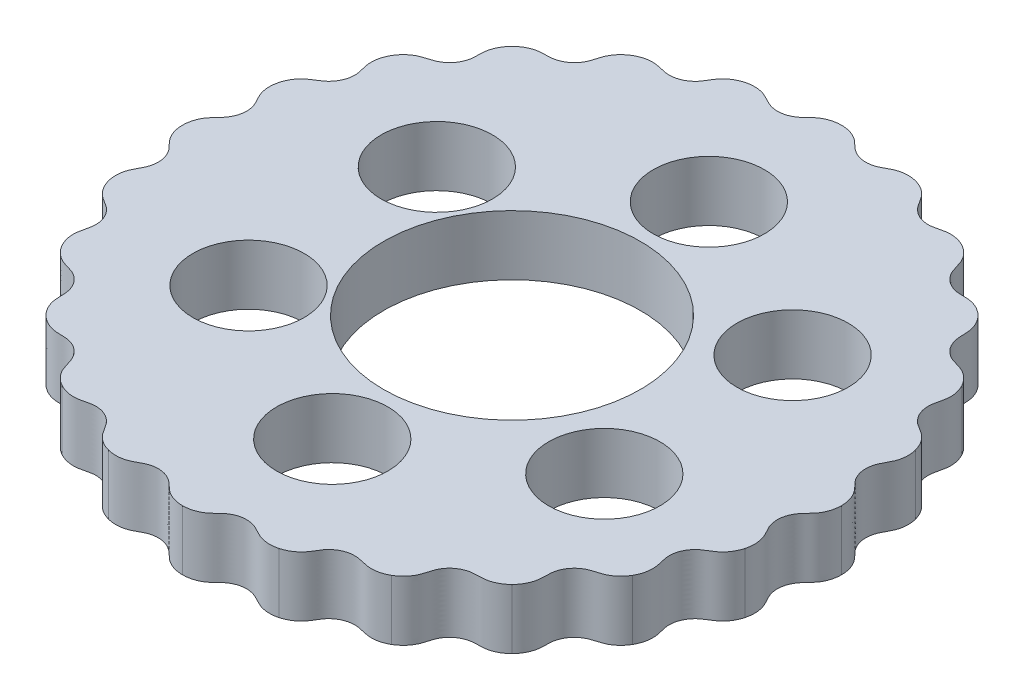
SolidWorks part; units mm, degrees
ref_plane "Front Plane" through (0, 0, 0) normal (0, 0, 1) x (1, 0, 0)
ref_plane "Top Plane" through (0, 0, 0) normal (0, 1, 0) x (1, 0, 0)
ref_plane "Right Plane" through (0, 0, 0) normal (1, 0, 0) x (0, 0, -1)
sketch "Sketch1" plane through (0, 0, 0) normal (0, 1, 0) x (1, 0, 0)
  line L0 (0, 0) -> (-1, 0) construction
  line L1 (40, 0) -> (41, 0) construction
  line L2 (-1, 0) -> (-1, 23) construction
  circle A0 centre (0, 0) radius 40 construction
  circle A1 centre (40, 0) radius 2.5 construction
  circle A2 centre (38.7433, -9.9476) radius 2.5 construction
  circle A3 centre (35.0523, -19.2701) radius 2.5 construction
  circle A4 centre (29.1587, -27.3819) radius 2.5 construction
  circle A5 centre (21.4331, -33.7731) radius 2.5 construction
  circle A6 centre (12.3607, -38.0423) radius 2.5 construction
  circle A7 centre (2.5116, -39.9211) radius 2.5 construction
  circle A8 centre (-7.4953, -39.2915) radius 2.5 construction
  circle A9 centre (-17.0312, -36.1931) radius 2.5 construction
  circle A10 centre (-25.497, -30.8205) radius 2.5 construction
  circle A11 centre (-32.3607, -23.5114) radius 2.5 construction
  circle A12 centre (-37.1911, -14.725) radius 2.5 construction
  circle A13 centre (-39.6846, -5.0133) radius 2.5 construction
  circle A14 centre (-39.6846, 5.0133) radius 2.5 construction
  circle A15 centre (-37.1911, 14.725) radius 2.5 construction
  circle A16 centre (-32.3607, 23.5114) radius 2.5 construction
  circle A17 centre (-25.497, 30.8205) radius 2.5 construction
  circle A18 centre (-17.0312, 36.1931) radius 2.5 construction
  circle A19 centre (-7.4953, 39.2915) radius 2.5 construction
  circle A20 centre (2.5116, 39.9211) radius 2.5 construction
  circle A21 centre (12.3607, 38.0423) radius 2.5 construction
  circle A22 centre (21.4331, 33.7731) radius 2.5 construction
  circle A23 centre (29.1587, 27.3819) radius 2.5 construction
  circle A24 centre (35.0523, 19.2701) radius 2.5 construction
  circle A25 centre (38.7433, 9.9476) radius 2.5 construction
  circle A26 centre (0, 0) radius 38.4 construction
  circle A27 centre (38.637, 10.3528) radius 1.6 construction
  circle A28 centre (39.603, 10.6116) radius 0.25 construction
  circle A29 centre (-1, 0) radius 15
  circle A30 centre (-1, 23) radius 6.5
  circle A31 centre (19.4186, 12.366) radius 6.5
  circle A32 centre (20.4186, -10.634) radius 6.5
  circle A33 centre (1, -23) radius 6.5
  circle A34 centre (-19.4186, -12.366) radius 6.5
  circle A35 centre (-20.4186, 10.634) radius 6.5
  spline S48 degree 3 poles (-38.1881, 9.9647) (-38.1134, 10.2441) (-37.9518, 10.654) (-37.653, 11.1446) (-37.3903, 11.4799) (-37.1455, 11.7256) (-36.9277, 11.9083) (-36.7529, 12.0385) (-36.5906, 12.1462) (-36.4589, 12.2267) (-36.305, 12.3174) (-36.1077, 12.438) (-35.8562, 12.5947) (-35.414, 12.9369) (-35.0082, 13.4243) (-34.7303, 13.9227) (-34.557, 14.4369) (-34.4576, 15.2234) (-34.5769, 15.8673) (-34.6328, 16.0713) (-34.6733, 16.2389) (-34.7113, 16.3925) (-34.7527, 16.5721) (-34.7948, 16.7807) (-34.8258, 16.9881) (-34.85, 17.2627) (-34.8492, 17.6154) (-34.7979, 18.0376) (-34.6627, 18.5948) (-34.4867, 18.9996) (-34.3419, 19.2502) knots -0.000084 -0.000084 -0.000084 -0.000084 0.124937 0.187447 0.249958 0.312468 0.343724 0.374979 0.406234 0.421862 0.437489 0.453117 0.468745 0.484372 0.492186 0.5 0.507814 0.515628 0.531255 0.546883 0.562511 0.578138 0.593766 0.625021 0.656276 0.687532 0.750042 0.812553 0.875063 1.000084 1.000084 1.000084 1.000084
  spline S49 degree 3 poles (-34.3419, 19.2502) (-34.1974, 19.5007) (-33.9353, 19.8548) (-33.5196, 20.2513) (-33.1791, 20.5073) (-32.879, 20.6812) (-32.6214, 20.8013) (-32.4189, 20.8818) (-32.2342, 20.9438) (-32.0861, 20.9876) (-31.914, 21.0353) (-31.6923, 21.1008) (-31.4088, 21.187) (-30.893, 21.4031) (-30.3749, 21.7688) (-29.9775, 22.1783) (-29.677, 22.6302) (-29.3775, 23.3642) (-29.326, 24.017) (-29.3272, 24.2285) (-29.323, 24.4009) (-29.3199, 24.559) (-29.3134, 24.7432) (-29.3001, 24.9557) (-29.2764, 25.164) (-29.2287, 25.4355) (-29.1366, 25.776) (-28.9778, 26.1705) (-28.703, 26.6737) (-28.4282, 27.0192) (-28.2235, 27.2237) knots -0.000084 -0.000084 -0.000084 -0.000084 0.124937 0.187447 0.249958 0.312468 0.343724 0.374979 0.406234 0.421862 0.437489 0.453117 0.468745 0.484372 0.492186 0.5 0.507814 0.515628 0.531255 0.546883 0.562511 0.578138 0.593766 0.625021 0.656276 0.687532 0.750042 0.812553 0.875063 1.000084 1.000084 1.000084 1.000084
  spline S50 degree 3 poles (-28.2235, 27.2237) (-28.0191, 27.4283) (-27.6742, 27.7026) (-27.1701, 27.978) (-26.7749, 28.1371) (-26.4401, 28.2274) (-26.1602, 28.2767) (-25.9437, 28.3021) (-25.7492, 28.3142) (-25.5949, 28.3181) (-25.4163, 28.3197) (-25.1852, 28.3255) (-24.889, 28.3354) (-24.3349, 28.4107) (-23.7398, 28.6298) (-23.25, 28.9226) (-22.8428, 29.2812) (-22.3634, 29.9127) (-22.1448, 30.5299) (-22.0912, 30.7346) (-22.0425, 30.9) (-21.9986, 31.0519) (-21.9447, 31.2282) (-21.8768, 31.43) (-21.8, 31.625) (-21.6836, 31.8749) (-21.5066, 32.18) (-21.251, 32.5199) (-20.8553, 32.9349) (-20.5005, 33.1974) (-20.2498, 33.3421) knots -0.000084 -0.000084 -0.000084 -0.000084 0.124937 0.187447 0.249958 0.312468 0.343724 0.374979 0.406234 0.421862 0.437489 0.453117 0.468745 0.484372 0.492186 0.5 0.507814 0.515628 0.531255 0.546883 0.562511 0.578138 0.593766 0.625021 0.656276 0.687532 0.750042 0.812553 0.875063 1.000084 1.000084 1.000084 1.000084
  spline S51 degree 3 poles (-20.2498, 33.3421) (-19.9994, 33.4868) (-19.5954, 33.6624) (-19.0372, 33.798) (-18.6143, 33.8494) (-18.2675, 33.85) (-17.9843, 33.8252) (-17.7687, 33.7936) (-17.5777, 33.755) (-17.4276, 33.7188) (-17.2547, 33.6741) (-17.0299, 33.6199) (-16.7413, 33.5529) (-16.1866, 33.4821) (-15.555, 33.5398) (-15.0061, 33.6958) (-14.52, 33.9368) (-13.8935, 34.4227) (-13.5226, 34.9623) (-13.4179, 35.1461) (-13.328, 35.2933) (-13.2462, 35.4287) (-13.1485, 35.585) (-13.0308, 35.7623) (-12.9061, 35.9308) (-12.729, 36.1421) (-12.479, 36.391) (-12.1442, 36.6532) (-11.6546, 36.9516) (-11.2439, 37.1134) (-10.9644, 37.1882) knots -0.000084 -0.000084 -0.000084 -0.000084 0.124937 0.187447 0.249958 0.312468 0.343724 0.374979 0.406234 0.421862 0.437489 0.453117 0.468745 0.484372 0.492186 0.5 0.507814 0.515628 0.531255 0.546883 0.562511 0.578138 0.593766 0.625021 0.656276 0.687532 0.750042 0.812553 0.875063 1.000084 1.000084 1.000084 1.000084
  spline S52 degree 3 poles (-10.9644, 37.1882) (-10.685, 37.2632) (-10.2493, 37.3283) (-9.675, 37.3147) (-9.2532, 37.2549) (-8.9181, 37.1657) (-8.651, 37.0685) (-8.4509, 36.9822) (-8.2764, 36.8954) (-8.1408, 36.8217) (-7.9853, 36.7337) (-7.7822, 36.6232) (-7.5208, 36.4837) (-7.0033, 36.2718) (-6.3783, 36.1641) (-5.8077, 36.1727) (-5.2758, 36.2797) (-4.5449, 36.5868) (-4.047, 37.0121) (-3.8982, 37.1625) (-3.7734, 37.2814) (-3.6593, 37.391) (-3.5245, 37.5167) (-3.3649, 37.6576) (-3.2008, 37.7881) (-2.9751, 37.9463) (-2.6692, 38.122) (-2.2779, 38.2886) (-1.7278, 38.4501) (-1.2892, 38.5001) (-0.9998, 38.5) knots -0.000084 -0.000084 -0.000084 -0.000084 0.124937 0.187447 0.249958 0.312468 0.343724 0.374979 0.406234 0.421862 0.437489 0.453117 0.468745 0.484372 0.492186 0.5 0.507814 0.515628 0.531255 0.546883 0.562511 0.578138 0.593766 0.625021 0.656276 0.687532 0.750042 0.812553 0.875063 1.000084 1.000084 1.000084 1.000084
  spline S53 degree 3 poles (-0.9998, 38.5) (-0.7106, 38.5001) (-0.2728, 38.4502) (0.2783, 38.2885) (0.6703, 38.1215) (0.9709, 37.9486) (1.2037, 37.7856) (1.3747, 37.6505) (1.5208, 37.5215) (1.6327, 37.4152) (1.7601, 37.29) (1.9277, 37.1307) (2.1441, 36.9283) (2.5891, 36.5896) (3.1649, 36.3238) (3.7182, 36.1844) (4.2598, 36.1501) (5.0452, 36.2577) (5.6363, 36.5395) (5.8189, 36.6464) (5.9703, 36.7289) (6.1088, 36.8053) (6.2716, 36.8918) (6.4622, 36.9865) (6.6544, 37.0701) (6.9134, 37.1645) (7.2543, 37.255) (7.6754, 37.3147) (8.2486, 37.3283) (8.6852, 37.2631) (8.9647, 37.1881) knots -0.000084 -0.000084 -0.000084 -0.000084 0.124937 0.187447 0.249958 0.312468 0.343724 0.374979 0.406234 0.421862 0.437489 0.453117 0.468745 0.484372 0.492186 0.5 0.507814 0.515628 0.531255 0.546883 0.562511 0.578138 0.593766 0.625021 0.656276 0.687532 0.750042 0.812553 0.875063 1.000084 1.000084 1.000084 1.000084
  spline S54 degree 3 poles (8.9647, 37.1881) (9.2441, 37.1134) (9.654, 36.9518) (10.1446, 36.653) (10.4799, 36.3903) (10.7256, 36.1455) (10.9083, 35.9277) (11.0385, 35.7529) (11.1462, 35.5906) (11.2267, 35.4589) (11.3174, 35.305) (11.438, 35.1077) (11.5947, 34.8562) (11.9369, 34.414) (12.4243, 34.0082) (12.9227, 33.7303) (13.4369, 33.557) (14.2234, 33.4576) (14.8673, 33.5769) (15.0713, 33.6328) (15.2389, 33.6733) (15.3925, 33.7113) (15.5721, 33.7527) (15.7807, 33.7948) (15.9881, 33.8258) (16.2627, 33.85) (16.6154, 33.8492) (17.0376, 33.7979) (17.5948, 33.6627) (17.9996, 33.4867) (18.2502, 33.3419) knots -0.000084 -0.000084 -0.000084 -0.000084 0.124937 0.187447 0.249958 0.312468 0.343724 0.374979 0.406234 0.421862 0.437489 0.453117 0.468745 0.484372 0.492186 0.5 0.507814 0.515628 0.531255 0.546883 0.562511 0.578138 0.593766 0.625021 0.656276 0.687532 0.750042 0.812553 0.875063 1.000084 1.000084 1.000084 1.000084
  spline S55 degree 3 poles (18.2502, 33.3419) (18.5007, 33.1974) (18.8548, 32.9353) (19.2513, 32.5196) (19.5073, 32.1791) (19.6812, 31.879) (19.8013, 31.6214) (19.8818, 31.4189) (19.9438, 31.2342) (19.9876, 31.0861) (20.0353, 30.914) (20.1008, 30.6923) (20.187, 30.4088) (20.4031, 29.893) (20.7688, 29.3749) (21.1783, 28.9775) (21.6302, 28.677) (22.3642, 28.3775) (23.017, 28.326) (23.2285, 28.3272) (23.4009, 28.323) (23.559, 28.3199) (23.7432, 28.3134) (23.9557, 28.3001) (24.164, 28.2764) (24.4355, 28.2287) (24.776, 28.1366) (25.1705, 27.9778) (25.6737, 27.703) (26.0192, 27.4282) (26.2237, 27.2235) knots -0.000084 -0.000084 -0.000084 -0.000084 0.124937 0.187447 0.249958 0.312468 0.343724 0.374979 0.406234 0.421862 0.437489 0.453117 0.468745 0.484372 0.492186 0.5 0.507814 0.515628 0.531255 0.546883 0.562511 0.578138 0.593766 0.625021 0.656276 0.687532 0.750042 0.812553 0.875063 1.000084 1.000084 1.000084 1.000084
  spline S56 degree 3 poles (26.2237, 27.2235) (26.4283, 27.0191) (26.7026, 26.6742) (26.978, 26.1701) (27.1371, 25.7749) (27.2274, 25.4401) (27.2767, 25.1602) (27.3021, 24.9437) (27.3142, 24.7492) (27.3181, 24.5949) (27.3197, 24.4163) (27.3255, 24.1852) (27.3354, 23.889) (27.4107, 23.3349) (27.6298, 22.7398) (27.9226, 22.25) (28.2812, 21.8428) (28.9127, 21.3634) (29.5299, 21.1448) (29.7346, 21.0912) (29.9, 21.0425) (30.0519, 20.9986) (30.2282, 20.9447) (30.43, 20.8768) (30.625, 20.8) (30.8749, 20.6836) (31.18, 20.5066) (31.5199, 20.251) (31.9349, 19.8553) (32.1974, 19.5005) (32.3421, 19.2498) knots -0.000084 -0.000084 -0.000084 -0.000084 0.124937 0.187447 0.249958 0.312468 0.343724 0.374979 0.406234 0.421862 0.437489 0.453117 0.468745 0.484372 0.492186 0.5 0.507814 0.515628 0.531255 0.546883 0.562511 0.578138 0.593766 0.625021 0.656276 0.687532 0.750042 0.812553 0.875063 1.000084 1.000084 1.000084 1.000084
  spline S57 degree 3 poles (32.3421, 19.2498) (32.4868, 18.9994) (32.6624, 18.5954) (32.798, 18.0372) (32.8494, 17.6143) (32.85, 17.2675) (32.8252, 16.9843) (32.7936, 16.7687) (32.755, 16.5777) (32.7188, 16.4276) (32.6741, 16.2547) (32.6199, 16.0299) (32.5529, 15.7413) (32.4821, 15.1866) (32.5398, 14.555) (32.6958, 14.0061) (32.9368, 13.52) (33.4227, 12.8935) (33.9623, 12.5226) (34.1461, 12.4179) (34.2933, 12.328) (34.4287, 12.2462) (34.585, 12.1485) (34.7623, 12.0308) (34.9308, 11.9061) (35.1421, 11.729) (35.391, 11.479) (35.6532, 11.1442) (35.9516, 10.6546) (36.1134, 10.2439) (36.1882, 9.9644) knots -0.000084 -0.000084 -0.000084 -0.000084 0.124937 0.187447 0.249958 0.312468 0.343724 0.374979 0.406234 0.421862 0.437489 0.453117 0.468745 0.484372 0.492186 0.5 0.507814 0.515628 0.531255 0.546883 0.562511 0.578138 0.593766 0.625021 0.656276 0.687532 0.750042 0.812553 0.875063 1.000084 1.000084 1.000084 1.000084
  spline S58 degree 3 poles (36.1882, 9.9644) (36.2632, 9.685) (36.3283, 9.2493) (36.3147, 8.675) (36.2549, 8.2532) (36.1657, 7.9181) (36.0685, 7.651) (35.9822, 7.4509) (35.8954, 7.2764) (35.8217, 7.1408) (35.7337, 6.9853) (35.6232, 6.7822) (35.4837, 6.5208) (35.2718, 6.0033) (35.1641, 5.3783) (35.1727, 4.8077) (35.2797, 4.2758) (35.5868, 3.5449) (36.0121, 3.047) (36.1625, 2.8982) (36.2814, 2.7734) (36.391, 2.6593) (36.5167, 2.5245) (36.6576, 2.3649) (36.7881, 2.2008) (36.9463, 1.9751) (37.122, 1.6692) (37.2886, 1.2779) (37.4501, 0.7278) (37.5001, 0.2892) (37.5, -0.0002) knots -0.000084 -0.000084 -0.000084 -0.000084 0.124937 0.187447 0.249958 0.312468 0.343724 0.374979 0.406234 0.421862 0.437489 0.453117 0.468745 0.484372 0.492186 0.5 0.507814 0.515628 0.531255 0.546883 0.562511 0.578138 0.593766 0.625021 0.656276 0.687532 0.750042 0.812553 0.875063 1.000084 1.000084 1.000084 1.000084
  spline S59 degree 3 poles (37.5, -0.0002) (37.5001, -0.2894) (37.4502, -0.7272) (37.2885, -1.2783) (37.1215, -1.6703) (36.9486, -1.9709) (36.7856, -2.2037) (36.6505, -2.3747) (36.5215, -2.5208) (36.4152, -2.6327) (36.29, -2.7601) (36.1307, -2.9277) (35.9283, -3.1441) (35.5896, -3.5891) (35.3238, -4.1649) (35.1844, -4.7182) (35.1501, -5.2598) (35.2577, -6.0452) (35.5395, -6.6363) (35.6464, -6.8189) (35.7289, -6.9703) (35.8053, -7.1088) (35.8918, -7.2716) (35.9865, -7.4622) (36.0701, -7.6544) (36.1645, -7.9134) (36.255, -8.2543) (36.3147, -8.6754) (36.3283, -9.2486) (36.2631, -9.6852) (36.1881, -9.9647) knots -0.000084 -0.000084 -0.000084 -0.000084 0.124937 0.187447 0.249958 0.312468 0.343724 0.374979 0.406234 0.421862 0.437489 0.453117 0.468745 0.484372 0.492186 0.5 0.507814 0.515628 0.531255 0.546883 0.562511 0.578138 0.593766 0.625021 0.656276 0.687532 0.750042 0.812553 0.875063 1.000084 1.000084 1.000084 1.000084
  spline S60 degree 3 poles (36.1881, -9.9647) (36.1134, -10.2441) (35.9518, -10.654) (35.653, -11.1446) (35.3903, -11.4799) (35.1455, -11.7256) (34.9277, -11.9083) (34.7529, -12.0385) (34.5906, -12.1462) (34.4589, -12.2267) (34.305, -12.3174) (34.1077, -12.438) (33.8562, -12.5947) (33.414, -12.9369) (33.0082, -13.4243) (32.7303, -13.9227) (32.557, -14.4369) (32.4576, -15.2234) (32.5769, -15.8673) (32.6328, -16.0713) (32.6733, -16.2389) (32.7113, -16.3925) (32.7527, -16.5721) (32.7948, -16.7807) (32.8258, -16.9881) (32.85, -17.2627) (32.8492, -17.6154) (32.7979, -18.0376) (32.6627, -18.5948) (32.4867, -18.9996) (32.3419, -19.2502) knots -0.000084 -0.000084 -0.000084 -0.000084 0.124937 0.187447 0.249958 0.312468 0.343724 0.374979 0.406234 0.421862 0.437489 0.453117 0.468745 0.484372 0.492186 0.5 0.507814 0.515628 0.531255 0.546883 0.562511 0.578138 0.593766 0.625021 0.656276 0.687532 0.750042 0.812553 0.875063 1.000084 1.000084 1.000084 1.000084
  spline S61 degree 3 poles (32.3419, -19.2502) (32.1974, -19.5007) (31.9353, -19.8548) (31.5196, -20.2513) (31.1791, -20.5073) (30.879, -20.6812) (30.6214, -20.8013) (30.4189, -20.8818) (30.2342, -20.9438) (30.0861, -20.9876) (29.914, -21.0353) (29.6923, -21.1008) (29.4088, -21.187) (28.893, -21.4031) (28.3749, -21.7688) (27.9775, -22.1783) (27.677, -22.6302) (27.3775, -23.3642) (27.326, -24.017) (27.3272, -24.2285) (27.323, -24.4009) (27.3199, -24.559) (27.3134, -24.7432) (27.3001, -24.9557) (27.2764, -25.164) (27.2287, -25.4355) (27.1366, -25.776) (26.9778, -26.1705) (26.703, -26.6737) (26.4282, -27.0192) (26.2235, -27.2237) knots -0.000084 -0.000084 -0.000084 -0.000084 0.124937 0.187447 0.249958 0.312468 0.343724 0.374979 0.406234 0.421862 0.437489 0.453117 0.468745 0.484372 0.492186 0.5 0.507814 0.515628 0.531255 0.546883 0.562511 0.578138 0.593766 0.625021 0.656276 0.687532 0.750042 0.812553 0.875063 1.000084 1.000084 1.000084 1.000084
  spline S62 degree 3 poles (26.2235, -27.2237) (26.0191, -27.4283) (25.6742, -27.7026) (25.1701, -27.978) (24.7749, -28.1371) (24.4401, -28.2274) (24.1602, -28.2767) (23.9437, -28.3021) (23.7492, -28.3142) (23.5949, -28.3181) (23.4163, -28.3197) (23.1852, -28.3255) (22.889, -28.3354) (22.3349, -28.4107) (21.7398, -28.6298) (21.25, -28.9226) (20.8428, -29.2812) (20.3634, -29.9127) (20.1448, -30.5299) (20.0912, -30.7346) (20.0425, -30.9) (19.9986, -31.0519) (19.9447, -31.2282) (19.8768, -31.43) (19.8, -31.625) (19.6836, -31.8749) (19.5066, -32.18) (19.251, -32.5199) (18.8553, -32.9349) (18.5005, -33.1974) (18.2498, -33.3421) knots -0.000084 -0.000084 -0.000084 -0.000084 0.124937 0.187447 0.249958 0.312468 0.343724 0.374979 0.406234 0.421862 0.437489 0.453117 0.468745 0.484372 0.492186 0.5 0.507814 0.515628 0.531255 0.546883 0.562511 0.578138 0.593766 0.625021 0.656276 0.687532 0.750042 0.812553 0.875063 1.000084 1.000084 1.000084 1.000084
  spline S63 degree 3 poles (18.2498, -33.3421) (17.9994, -33.4868) (17.5954, -33.6624) (17.0372, -33.798) (16.6143, -33.8494) (16.2675, -33.85) (15.9843, -33.8252) (15.7687, -33.7936) (15.5777, -33.755) (15.4276, -33.7188) (15.2547, -33.6741) (15.0299, -33.6199) (14.7413, -33.5529) (14.1866, -33.4821) (13.555, -33.5398) (13.0061, -33.6958) (12.52, -33.9368) (11.8935, -34.4227) (11.5226, -34.9623) (11.4179, -35.1461) (11.328, -35.2933) (11.2462, -35.4287) (11.1485, -35.585) (11.0308, -35.7623) (10.9061, -35.9308) (10.729, -36.1421) (10.479, -36.391) (10.1442, -36.6532) (9.6546, -36.9516) (9.2439, -37.1134) (8.9644, -37.1882) knots -0.000084 -0.000084 -0.000084 -0.000084 0.124937 0.187447 0.249958 0.312468 0.343724 0.374979 0.406234 0.421862 0.437489 0.453117 0.468745 0.484372 0.492186 0.5 0.507814 0.515628 0.531255 0.546883 0.562511 0.578138 0.593766 0.625021 0.656276 0.687532 0.750042 0.812553 0.875063 1.000084 1.000084 1.000084 1.000084
  spline S64 degree 3 poles (8.9644, -37.1882) (8.685, -37.2632) (8.2493, -37.3283) (7.675, -37.3147) (7.2532, -37.2549) (6.9181, -37.1657) (6.651, -37.0685) (6.4509, -36.9822) (6.2764, -36.8954) (6.1408, -36.8217) (5.9853, -36.7337) (5.7822, -36.6232) (5.5208, -36.4837) (5.0033, -36.2718) (4.3783, -36.1641) (3.8077, -36.1727) (3.2758, -36.2797) (2.5449, -36.5868) (2.047, -37.0121) (1.8982, -37.1625) (1.7734, -37.2814) (1.6593, -37.391) (1.5245, -37.5167) (1.3649, -37.6576) (1.2008, -37.7881) (0.9751, -37.9463) (0.6692, -38.122) (0.2779, -38.2886) (-0.2722, -38.4501) (-0.7108, -38.5001) (-1.0002, -38.5) knots -0.000084 -0.000084 -0.000084 -0.000084 0.124937 0.187447 0.249958 0.312468 0.343724 0.374979 0.406234 0.421862 0.437489 0.453117 0.468745 0.484372 0.492186 0.5 0.507814 0.515628 0.531255 0.546883 0.562511 0.578138 0.593766 0.625021 0.656276 0.687532 0.750042 0.812553 0.875063 1.000084 1.000084 1.000084 1.000084
  spline S65 degree 3 poles (-1.0002, -38.5) (-1.2894, -38.5001) (-1.7272, -38.4502) (-2.2783, -38.2885) (-2.6703, -38.1215) (-2.9709, -37.9486) (-3.2037, -37.7856) (-3.3747, -37.6505) (-3.5208, -37.5215) (-3.6327, -37.4152) (-3.7601, -37.29) (-3.9277, -37.1307) (-4.1441, -36.9283) (-4.5891, -36.5896) (-5.1649, -36.3238) (-5.7182, -36.1844) (-6.2598, -36.1501) (-7.0452, -36.2577) (-7.6363, -36.5395) (-7.8189, -36.6464) (-7.9703, -36.7289) (-8.1088, -36.8053) (-8.2716, -36.8918) (-8.4622, -36.9865) (-8.6544, -37.0701) (-8.9134, -37.1645) (-9.2543, -37.255) (-9.6754, -37.3147) (-10.2486, -37.3283) (-10.6852, -37.2631) (-10.9647, -37.1881) knots -0.000084 -0.000084 -0.000084 -0.000084 0.124937 0.187447 0.249958 0.312468 0.343724 0.374979 0.406234 0.421862 0.437489 0.453117 0.468745 0.484372 0.492186 0.5 0.507814 0.515628 0.531255 0.546883 0.562511 0.578138 0.593766 0.625021 0.656276 0.687532 0.750042 0.812553 0.875063 1.000084 1.000084 1.000084 1.000084
  spline S66 degree 3 poles (-10.9647, -37.1881) (-11.2441, -37.1134) (-11.654, -36.9518) (-12.1446, -36.653) (-12.4799, -36.3903) (-12.7256, -36.1455) (-12.9083, -35.9277) (-13.0385, -35.7529) (-13.1462, -35.5906) (-13.2267, -35.4589) (-13.3174, -35.305) (-13.438, -35.1077) (-13.5947, -34.8562) (-13.9369, -34.414) (-14.4243, -34.0082) (-14.9227, -33.7303) (-15.4369, -33.557) (-16.2234, -33.4576) (-16.8673, -33.5769) (-17.0713, -33.6328) (-17.2389, -33.6733) (-17.3925, -33.7113) (-17.5721, -33.7527) (-17.7807, -33.7948) (-17.9881, -33.8258) (-18.2627, -33.85) (-18.6154, -33.8492) (-19.0376, -33.7979) (-19.5948, -33.6627) (-19.9996, -33.4867) (-20.2502, -33.3419) knots -0.000084 -0.000084 -0.000084 -0.000084 0.124937 0.187447 0.249958 0.312468 0.343724 0.374979 0.406234 0.421862 0.437489 0.453117 0.468745 0.484372 0.492186 0.5 0.507814 0.515628 0.531255 0.546883 0.562511 0.578138 0.593766 0.625021 0.656276 0.687532 0.750042 0.812553 0.875063 1.000084 1.000084 1.000084 1.000084
  spline S67 degree 3 poles (-20.2502, -33.3419) (-20.5007, -33.1974) (-20.8548, -32.9353) (-21.2513, -32.5196) (-21.5073, -32.1791) (-21.6812, -31.879) (-21.8013, -31.6214) (-21.8818, -31.4189) (-21.9438, -31.2342) (-21.9876, -31.0861) (-22.0353, -30.914) (-22.1008, -30.6923) (-22.187, -30.4088) (-22.4031, -29.893) (-22.7688, -29.3749) (-23.1783, -28.9775) (-23.6302, -28.677) (-24.3642, -28.3775) (-25.017, -28.326) (-25.2285, -28.3272) (-25.4009, -28.323) (-25.559, -28.3199) (-25.7432, -28.3134) (-25.9557, -28.3001) (-26.164, -28.2764) (-26.4355, -28.2287) (-26.776, -28.1366) (-27.1705, -27.9778) (-27.6737, -27.703) (-28.0192, -27.4282) (-28.2237, -27.2235) knots -0.000084 -0.000084 -0.000084 -0.000084 0.124937 0.187447 0.249958 0.312468 0.343724 0.374979 0.406234 0.421862 0.437489 0.453117 0.468745 0.484372 0.492186 0.5 0.507814 0.515628 0.531255 0.546883 0.562511 0.578138 0.593766 0.625021 0.656276 0.687532 0.750042 0.812553 0.875063 1.000084 1.000084 1.000084 1.000084
  spline S68 degree 3 poles (-28.2237, -27.2235) (-28.4283, -27.0191) (-28.7026, -26.6742) (-28.978, -26.1701) (-29.1371, -25.7749) (-29.2274, -25.4401) (-29.2767, -25.1602) (-29.3021, -24.9437) (-29.3142, -24.7492) (-29.3181, -24.5949) (-29.3197, -24.4163) (-29.3255, -24.1852) (-29.3354, -23.889) (-29.4107, -23.3349) (-29.6298, -22.7398) (-29.9226, -22.25) (-30.2812, -21.8428) (-30.9127, -21.3634) (-31.5299, -21.1448) (-31.7346, -21.0912) (-31.9, -21.0425) (-32.0519, -20.9986) (-32.2282, -20.9447) (-32.43, -20.8768) (-32.625, -20.8) (-32.8749, -20.6836) (-33.18, -20.5066) (-33.5199, -20.251) (-33.9349, -19.8553) (-34.1974, -19.5005) (-34.3421, -19.2498) knots -0.000084 -0.000084 -0.000084 -0.000084 0.124937 0.187447 0.249958 0.312468 0.343724 0.374979 0.406234 0.421862 0.437489 0.453117 0.468745 0.484372 0.492186 0.5 0.507814 0.515628 0.531255 0.546883 0.562511 0.578138 0.593766 0.625021 0.656276 0.687532 0.750042 0.812553 0.875063 1.000084 1.000084 1.000084 1.000084
  spline S69 degree 3 poles (-34.3421, -19.2498) (-34.4868, -18.9994) (-34.6624, -18.5954) (-34.798, -18.0372) (-34.8494, -17.6143) (-34.85, -17.2675) (-34.8252, -16.9843) (-34.7936, -16.7687) (-34.755, -16.5777) (-34.7188, -16.4276) (-34.6741, -16.2547) (-34.6199, -16.0299) (-34.5529, -15.7413) (-34.4821, -15.1866) (-34.5398, -14.555) (-34.6958, -14.0061) (-34.9368, -13.52) (-35.4227, -12.8935) (-35.9623, -12.5226) (-36.1461, -12.4179) (-36.2933, -12.328) (-36.4287, -12.2462) (-36.585, -12.1485) (-36.7623, -12.0308) (-36.9308, -11.9061) (-37.1421, -11.729) (-37.391, -11.479) (-37.6532, -11.1442) (-37.9516, -10.6546) (-38.1134, -10.2439) (-38.1882, -9.9644) knots -0.000084 -0.000084 -0.000084 -0.000084 0.124937 0.187447 0.249958 0.312468 0.343724 0.374979 0.406234 0.421862 0.437489 0.453117 0.468745 0.484372 0.492186 0.5 0.507814 0.515628 0.531255 0.546883 0.562511 0.578138 0.593766 0.625021 0.656276 0.687532 0.750042 0.812553 0.875063 1.000084 1.000084 1.000084 1.000084
  spline S70 degree 3 poles (-38.1882, -9.9644) (-38.2632, -9.685) (-38.3283, -9.2493) (-38.3147, -8.675) (-38.2549, -8.2532) (-38.1657, -7.9181) (-38.0685, -7.651) (-37.9822, -7.4509) (-37.8954, -7.2764) (-37.8217, -7.1408) (-37.7337, -6.9853) (-37.6232, -6.7822) (-37.4837, -6.5208) (-37.2718, -6.0033) (-37.1641, -5.3783) (-37.1727, -4.8077) (-37.2797, -4.2758) (-37.5868, -3.5449) (-38.0121, -3.047) (-38.1625, -2.8982) (-38.2814, -2.7734) (-38.391, -2.6593) (-38.5167, -2.5245) (-38.6576, -2.3649) (-38.7881, -2.2008) (-38.9463, -1.9751) (-39.122, -1.6692) (-39.2886, -1.2779) (-39.4501, -0.7278) (-39.5001, -0.2892) (-39.5, 0.0002) knots -0.000084 -0.000084 -0.000084 -0.000084 0.124937 0.187447 0.249958 0.312468 0.343724 0.374979 0.406234 0.421862 0.437489 0.453117 0.468745 0.484372 0.492186 0.5 0.507814 0.515628 0.531255 0.546883 0.562511 0.578138 0.593766 0.625021 0.656276 0.687532 0.750042 0.812553 0.875063 1.000084 1.000084 1.000084 1.000084
  spline S71 degree 3 poles (-39.5, 0.0002) (-39.5001, 0.2894) (-39.4502, 0.7272) (-39.2885, 1.2783) (-39.1215, 1.6703) (-38.9486, 1.9709) (-38.7856, 2.2037) (-38.6505, 2.3747) (-38.5215, 2.5208) (-38.4152, 2.6327) (-38.29, 2.7601) (-38.1307, 2.9277) (-37.9283, 3.1441) (-37.5896, 3.5891) (-37.3238, 4.1649) (-37.1844, 4.7182) (-37.1501, 5.2598) (-37.2577, 6.0452) (-37.5395, 6.6363) (-37.6464, 6.8189) (-37.7289, 6.9703) (-37.8053, 7.1088) (-37.8918, 7.2716) (-37.9865, 7.4622) (-38.0701, 7.6544) (-38.1645, 7.9134) (-38.255, 8.2543) (-38.3147, 8.6754) (-38.3283, 9.2486) (-38.2631, 9.6852) (-38.1881, 9.9647) knots -0.000084 -0.000084 -0.000084 -0.000084 0.124937 0.187447 0.249958 0.312468 0.343724 0.374979 0.406234 0.421862 0.437489 0.453117 0.468745 0.484372 0.492186 0.5 0.507814 0.515628 0.531255 0.546883 0.562511 0.578138 0.593766 0.625021 0.656276 0.687532 0.750042 0.812553 0.875063 1.000084 1.000084 1.000084 1.000084
  point P55 (0, 0)
  point P60 (41, 0)
  point P63 (40.9002, 1.1207)
  point P64 (40.6184, 2.162)
  point P65 (40.204, 3.0594)
  point P66 (39.7289, 3.7751)
  point P67 (39.2742, 4.3054)
  point P68 (38.9149, 4.6811)
  point P69 (38.7057, 4.9619)
  point P70 (38.671, 5.2249)
  point P71 (38.8004, 5.5503)
  point P72 (39.0503, 6.0062)
  point P73 (39.3522, 6.6362)
  point P74 (39.6259, 7.4504)
  point P75 (39.794, 8.4245)
  point P76 (39.7966, 9.5032)
  point P77 (39.603, 10.6116)
  point P93 (0, 0)
  point P462 (0, 0)
  dimension "D1" = 80
  dimension "D2" = 5
  dimension "D4" = 76.8
  dimension "D6" = 0.5
  dimension "D8" = 30
  dimension "D10" = 13
  dimension "D3" = 1
  dimension "D5" = 1
  dimension "D9" = 23
  dimension "D7" = 25
  dimension "D11" = 6
extrude "Boss-Extrude1" add sketch "Sketch1" along normal blind 7
